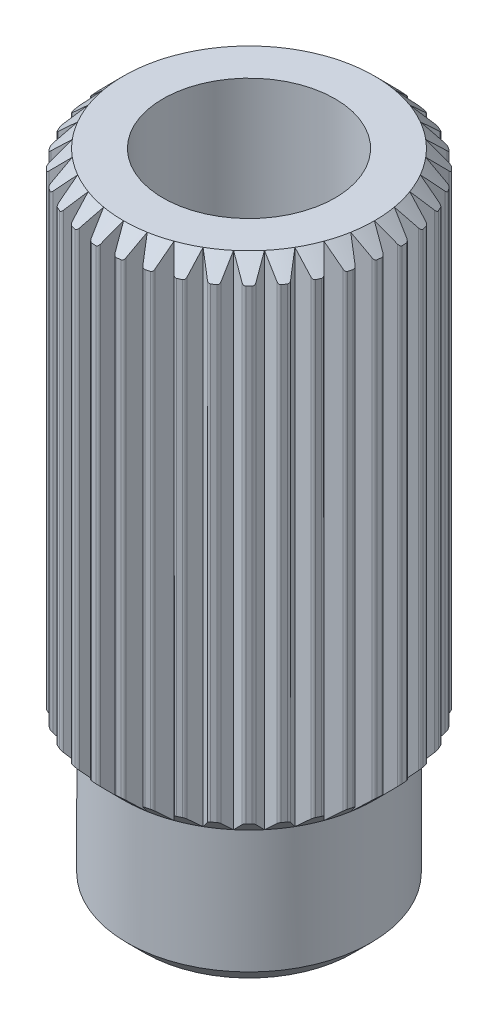
SolidWorks part; units mm, degrees
ref_plane "Front Plane" through (0, 0, 0) normal (0, 0, 1) x (1, 0, 0)
ref_plane "Top Plane" through (0, 0, 0) normal (0, 1, 0) x (1, 0, 0)
ref_plane "Right Plane" through (0, 0, 0) normal (1, 0, 0) x (0, 0, -1)
sketch "Sketch1" plane through (0, 0, 0) normal (0, 1, 0) x (1, 0, 0)
  circle A0 centre (0, 0) radius 5
  circle A1 centre (0, 0) radius 3
  dimension "D1" = 10
  dimension "D2" = 6
extrude "Boss-Extrude1" add sketch "Sketch1" along normal blind 22.5
sketch "Sketch2" plane through (0, 0, 0) normal (0, -1, 0) x (1, 0, 0)
  circle A0 centre (0, 0) radius 4.25
  circle A1 centre (0, 0) radius 5
extrude "Cut-Extrude1" cut sketch "Sketch2" against normal blind 5
chamfer "Chamfer1" distance 0.625 angle 45 3 edges at (0, 0, -4.25) (0, 22.5, 5) (0, 5, -5)
sketch "Sketch3" plane through (0, 22.5, 0) normal (0, 1, 0) x (1, 0, 0)
  line L0 (0, 0) -> (0, 4.375) construction
  line L1 (0, 4.375) -> (0, 5.0744) construction
  line L2 (0, 4.375) -> (0.329, 5.0806)
  line L3 (0, 4.375) -> (-0.329, 5.0806)
  line L4 (-0.329, 5.0806) -> (0.329, 5.0806)
  circle A0 centre (0, 0) radius 4.375 construction
  dimension "D1" = 25
extrude "Cut-Extrude2" cut sketch "Sketch3" against normal up to surface (17.5 mm away) up to face at (0, 5, -4.375)
fillet "Fillet1" radius 0.1 2 edges at (-0.2876, 13.75, -4.9917) (0.2876, 13.75, -4.9917)
pattern_circular "CirPattern2" count 36 over 360 about axis through (0, 0, 0) along (0, 1, 0) of "Cut-Extrude2", "Fillet1"
